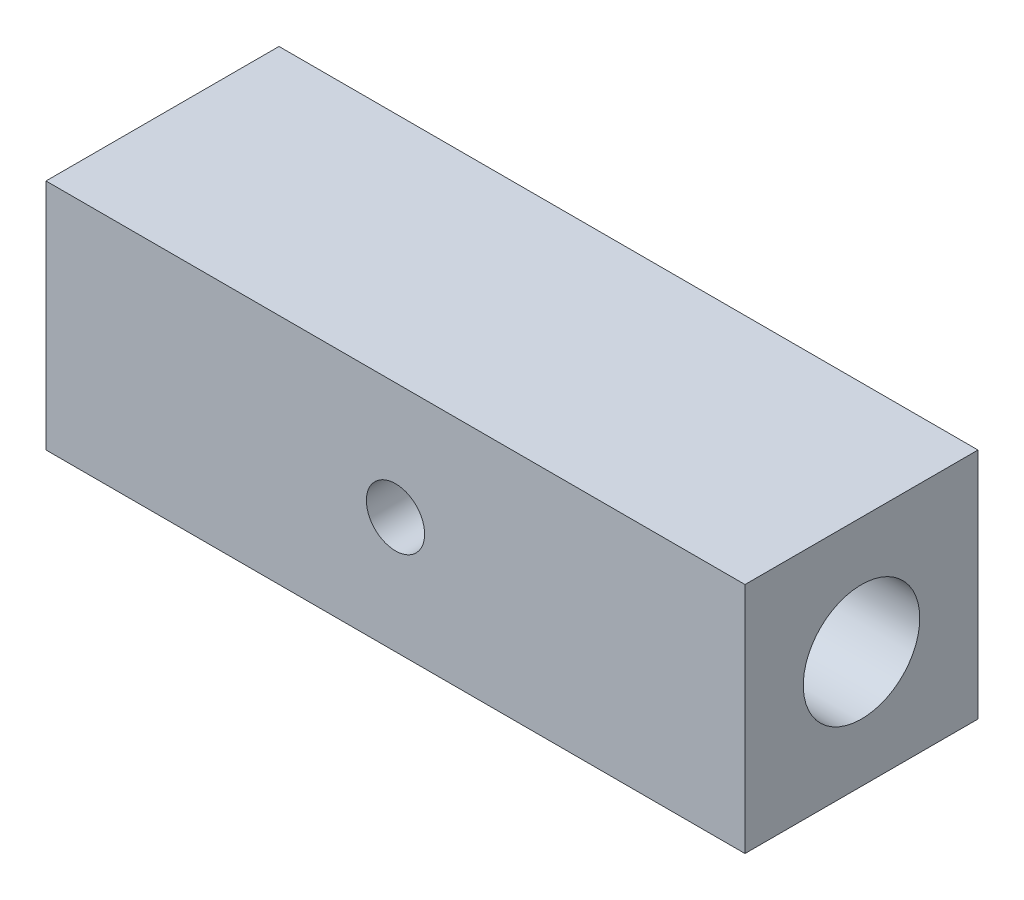
SolidWorks part; units mm, degrees
ref_plane "Front Plane" through (0, 0, 0) normal (0, 0, 1) x (1, 0, 0)
ref_plane "Top Plane" through (0, 0, 0) normal (0, 1, 0) x (1, 0, 0)
ref_plane "Right Plane" through (0, 0, 0) normal (1, 0, 0) x (0, 0, -1)
sketch "Sketch1" plane through (0, 0, 0) normal (0, 0, 1) x (1, 0, 0)
  line L1 (-76.2, 25.4) -> (0, 25.4)
  line L2 (-76.2, 25.4) -> (-76.2, 0)
  line L3 (-76.2, 0) -> (0, 0)
  line L4 (0, 25.4) -> (0, 0)
  circle A0 centre (-38.1, 12.7) radius 3.175
  dimension "D3" = 6.35
  dimension "D1" = 25.4
  dimension "D2" = 76.2
extrude "Boss-Extrude1" add sketch "Sketch1" along normal blind 25.4
sketch "Sketch2" plane through (0, 0, 0) normal (1, 0, 0) x (0, 0, -1)
  circle A0 centre (-12.7, 12.7) radius 6.35
  dimension "D1" = 12.7
extrude "Cut-Extrude1" cut sketch "Sketch2" against normal through all
scale "Scale1" scale about centroid uniform scaling yes scale factor 1.5
scale "Scale2" scale about centroid uniform scaling yes scale factor 0.67
